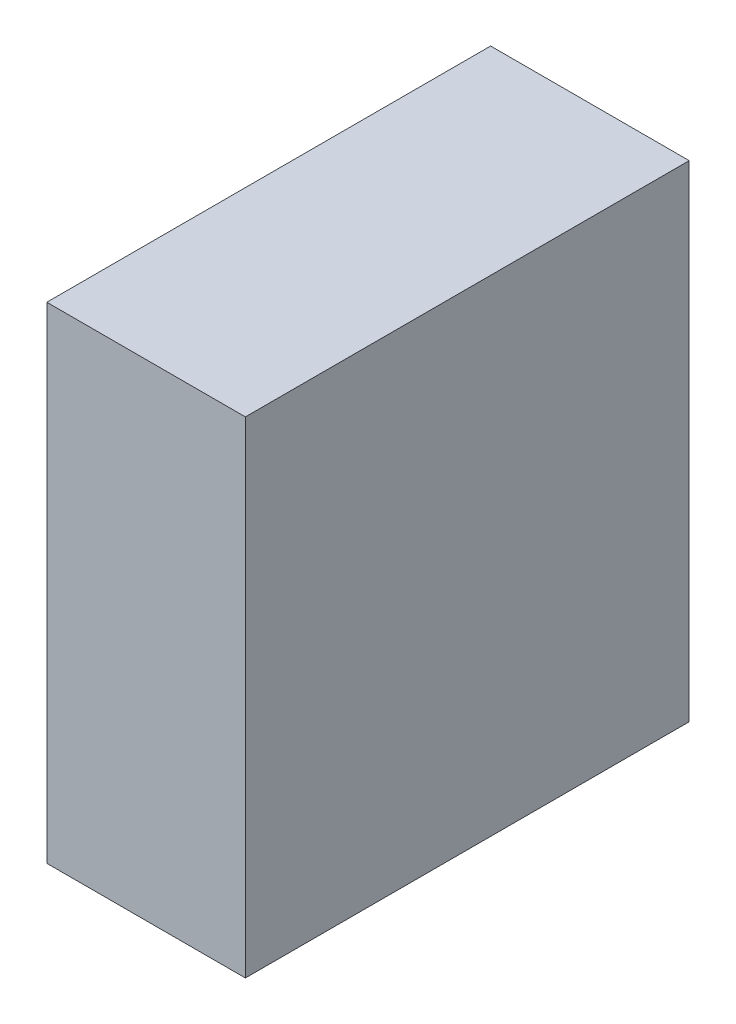
SolidWorks part; units mm, degrees
ref_plane "Front" through (0, 0, 0) normal (0, 0, 1) x (1, 0, 0)
ref_plane "Top" through (0, 0, 0) normal (0, 1, 0) x (1, 0, 0)
ref_plane "Right" through (0, 0, 0) normal (1, 0, 0) x (0, 0, -1)
sketch "Sketch1" plane through (0, 0, 0) normal (0, 1, 0) x (1, 0, 0)
  line L0 (0, 0) -> (613, 0)
  line L1 (0, 0) -> (0, 1370)
  line L2 (0, 1370) -> (613, 1370)
  line L3 (613, 0) -> (613, 1370)
  dimension "D1" = 613
  dimension "D2" = 1370
extrude "Boss-Extrude1" add sketch "Sketch1" along normal blind 1500
equation "\"Height\"= 1500"
equation "\"D1@Boss-Extrude1\"=\"Height\""
